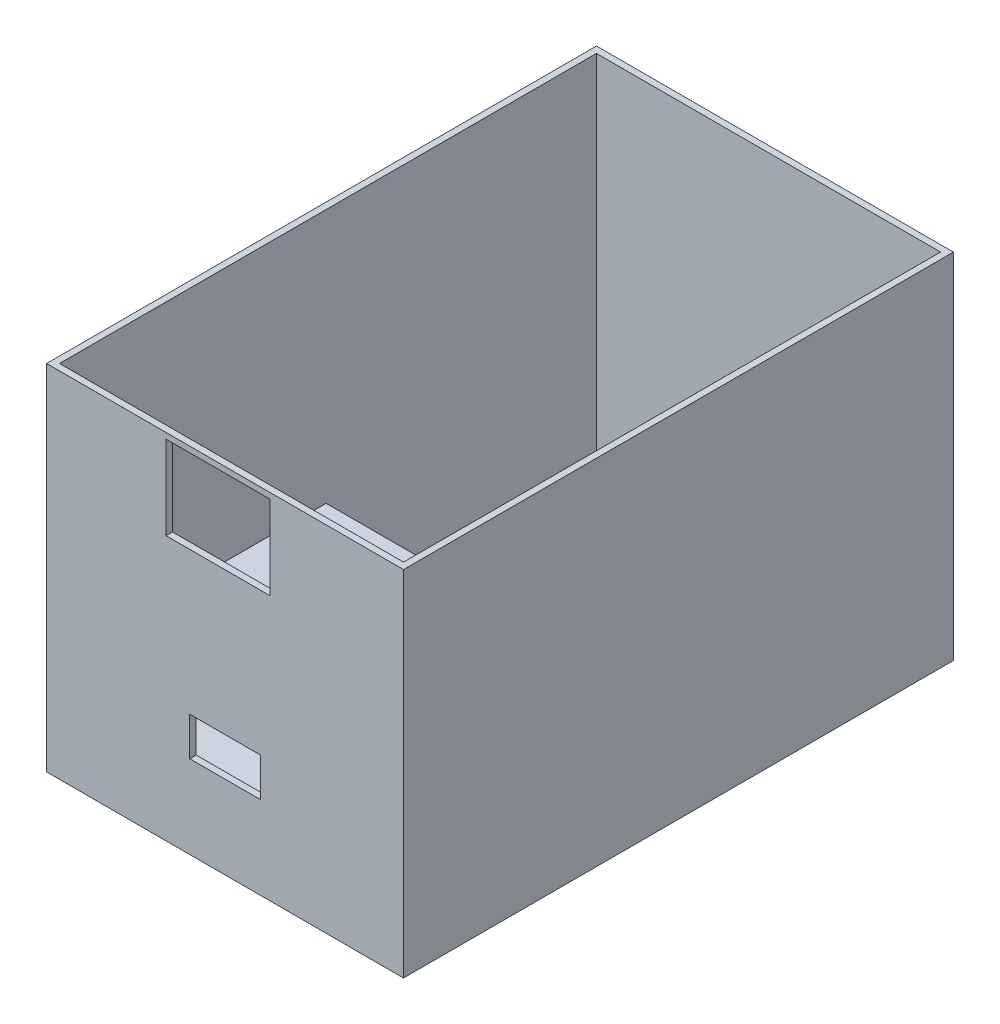
SolidWorks part; units mm, degrees
ref_plane "Front Plane" through (0, 0, 0) normal (0, 0, 1) x (1, 0, 0)
ref_plane "Top Plane" through (0, 0, 0) normal (0, 1, 0) x (1, 0, 0)
ref_plane "Right Plane" through (0, 0, 0) normal (1, 0, 0) x (0, 0, -1)
sketch "Sketch1" plane through (0, 0, 0) normal (0, 1, 0) x (1, 0, 0)
  line L1 (-27.75, 42.75) -> (27.75, 42.75)
  line L2 (-27.75, 42.75) -> (-27.75, -42.75)
  line L3 (-27.75, -42.75) -> (27.75, -42.75)
  line L4 (27.75, 42.75) -> (27.75, -42.75)
  line L5 (-27.75, 42.75) -> (27.75, -42.75) construction
  line L6 (-27.75, -42.75) -> (27.75, 42.75) construction
  line L7 (-26.75, -41.75) -> (26.75, -41.75)
  line L8 (-26.75, -41.75) -> (-26.75, 41.75)
  line L9 (-26.75, 41.75) -> (26.75, 41.75)
  line L10 (26.75, -41.75) -> (26.75, 41.75)
  line L11 (-26.75, -41.75) -> (26.75, 41.75) construction
  line L12 (-26.75, 41.75) -> (26.75, -41.75) construction
  point P0 (0, 0)
  point P6 (0, 0)
  point P11 (0, 41.75)
  dimension "D1" = 85.5
  dimension "D2" = 55.5
  dimension "D3" = 1
  dimension "D4" = 1
extrude "Boss-Extrude1" add sketch "Sketch1" along normal blind 54 contours L8 L9 L10 L7 | L2 L3 L4 L1
sketch "Sketch2" plane through (0, 0, 0) normal (0, -1, 0) x (1, 0, 0)
  line L1 (-27.75, 42.75) -> (27.75, 42.75)
  line L2 (-27.75, 42.75) -> (-27.75, -42.75)
  line L3 (-27.75, -42.75) -> (27.75, -42.75)
  line L4 (27.75, 42.75) -> (27.75, -42.75)
extrude "Boss-Extrude2" add sketch "Sketch2" along normal blind 1
sketch "Sketch3" plane through (0, 0, 42.75) normal (0, 0, 1) x (1, 0, 0)
  line L0 (0, -1) -> (0, 54) construction
  line L1 (27.75, -1) -> (-27.75, -1) construction
  line L2 (-27.75, 54) -> (27.75, 54) construction
  line L4 (-5.5, 17.9) -> (5.5, 17.9)
  line L5 (-5.5, 17.9) -> (-5.5, 11.9)
  line L6 (-5.5, 11.9) -> (5.5, 11.9)
  line L7 (5.5, 17.9) -> (5.5, 11.9)
  line L8 (-5.5, 17.9) -> (5.5, 11.9) construction
  line L9 (-5.5, 11.9) -> (5.5, 17.9) construction
  point P6 (0, 14.9)
  point P11 (5.5, 14.9)
  dimension "D1" = 11
  dimension "D2" = 6
  dimension "D3" = 18.9
extrude "Cut-Extrude1" cut sketch "Sketch3" against normal blind 1
sketch "Sketch5" plane through (0, 0, 41.75) normal (0, 0, -1) x (-1, 0, 0)
  line L0 (-5.5, 17.9) -> (5.5, 17.9) construction
  line L1 (-14.7139, 25.9) -> (15.2861, 25.9)
  line L2 (-14.7139, 25.9) -> (-14.7139, 20.9)
  line L3 (-14.7139, 20.9) -> (15.2861, 20.9)
  line L4 (15.2861, 25.9) -> (15.2861, 20.9)
  line L5 (-14.7139, 25.9) -> (15.2861, 20.9) construction
  line L6 (-14.7139, 20.9) -> (15.2861, 25.9) construction
  point P0 (0.2861, 23.4)
  point P7 (0, 0)
  dimension "D1" = 5
  dimension "D2" = 30
  dimension "D3" = 3
extrude "Boss-Extrude4" add sketch "Sketch5" along normal blind 30
sketch "Sketch8" plane through (0, 0, 41.75) normal (0, 0, -1) x (-1, 0, 0)
  line L0 (15.2861, 25.9) -> (-14.7139, 25.9) construction
  line L1 (-7.0197, 53.1) -> (9.1803, 53.1)
  line L2 (-7.0197, 53.1) -> (-7.0197, 40.1)
  line L3 (-7.0197, 40.1) -> (9.1803, 40.1)
  line L4 (9.1803, 53.1) -> (9.1803, 40.1)
  line L5 (-7.0197, 53.1) -> (9.1803, 40.1) construction
  line L6 (-7.0197, 40.1) -> (9.1803, 53.1) construction
  point P0 (1.0803, 46.6)
  dimension "D1" = 13
  dimension "D2" = 16.2
  dimension "D3" = 27.2
extrude "Cut-Extrude3" cut sketch "Sketch8" against normal blind 1
